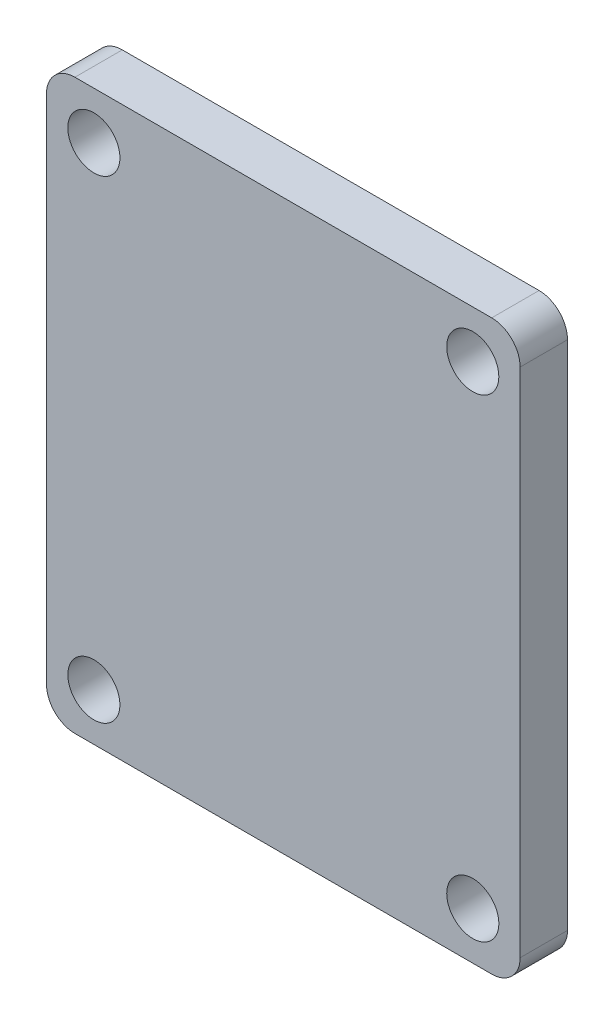
SolidWorks part; units mm, degrees
ref_plane "Front Plane" through (0, 0, 0) normal (0, 0, 1) x (1, 0, 0)
ref_plane "Top Plane" through (0, 0, 0) normal (0, 1, 0) x (1, 0, 0)
ref_plane "Right Plane" through (0, 0, 0) normal (1, 0, 0) x (0, 0, -1)
sketch "Sketch2" plane through (0, 0, 0) normal (0, 0, 1) x (1, 0, 0)
  line L0 (0, -3) -> (0, -57)
  line L1 (3, -60) -> (47, -60)
  line L2 (50, -57) -> (50, -3)
  line L3 (47, 0) -> (3, 0)
  line L4 (0, -30) -> (50, -30) construction
  circle A0 centre (5, -5) radius 2.75
  circle A1 centre (45, -5) radius 2.75
  circle A2 centre (45, -55) radius 2.75
  circle A3 centre (5, -55) radius 2.75
  arc A4 (0, -57) -> (3, -60) centre (3, -57) ccw
  arc A5 (47, -60) -> (50, -57) centre (47, -57) ccw
  arc A6 (50, -3) -> (47, 0) centre (47, -3) ccw
  arc A7 (0, -3) -> (3, 0) centre (3, -3) cw
  point P17 (0, -60)
  point P20 (50, -60)
  point P25 (0, 0)
  dimension "D3" = 5.5
  dimension "D4" = 5
  dimension "D5" = 5
  dimension "D6" = 5.5
  dimension "D7" = 5
  dimension "D8" = 5
  dimension "D9" = 3
  dimension "D1" = 60
  dimension "D2" = 50
extrude "Boss-Extrude1" add sketch "Sketch2" along normal blind 5
